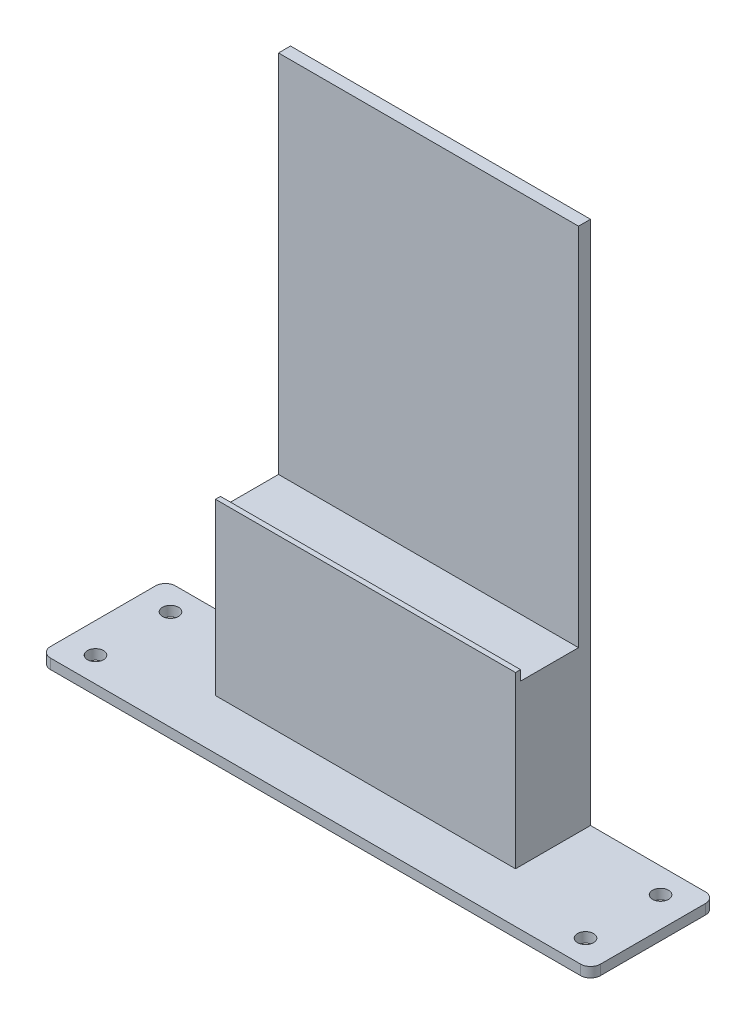
SolidWorks part; units mm, degrees
ref_plane "前视基准面" through (0, 0, 0) normal (0, 0, 1) x (1, 0, 0)
ref_plane "上视基准面" through (0, 0, 0) normal (0, 1, 0) x (1, 0, 0)
ref_plane "右视基准面" through (0, 0, 0) normal (1, 0, 0) x (0, 0, -1)
other "Configuration Table"
sketch "草图1" plane through (0, 0, 0) normal (0, 1, 0) x (1, 0, 0)
  line L0 (0, 0) -> (0, -50000) construction
  line L1 (-55, 12.5) -> (55, 12.5)
  line L2 (-55, 12.5) -> (-55, -12.5)
  line L3 (-55, -12.5) -> (55, -12.5)
  line L4 (55, 12.5) -> (55, -12.5)
  line L5 (-55, 12.5) -> (55, -12.5) construction
  line L6 (-55, -12.5) -> (55, 12.5) construction
  line L7 (0, 0) -> (-50000, 0) construction
  circle A0 centre (-49, 7.5) radius 1.6
  circle A1 centre (49, 7.5) radius 1.6
  circle A2 centre (49, -7.5) radius 1.6
  circle A3 centre (-49, -7.5) radius 1.6
  point P0 (0, 0)
  dimension "D3" = 3.2
  dimension "D1" = 110
  dimension "D2" = 25
  dimension "D4" = 15
  dimension "D5" = 98
extrude "凸台-拉伸1" add sketch "草图1" along normal blind 2
ref_plane "基准面1" through (0, 115, 0) normal (0, 1, 0) x (1, 0, 0)
sketch "草图2" plane through (0, 115, 0) normal (0, 1, 0) x (1, 0, 0)
  line L0 (55, 12.5) -> (-55, 12.5) construction
  line L1 (0, 0) -> (0, -50000) construction
  line L2 (-30, 12.5) -> (-30, -2.5)
  line L3 (-30, -2.5) -> (30, -2.5)
  line L4 (30, -2.5) -> (30, 12.5)
  line L5 (30, 12.5) -> (-30, 12.5)
  point P0 (-30, 12.5)
  point P6 (30, 12.5)
  dimension "D1" = 60
  dimension "D2" = 15
extrude "凸台-拉伸2" add sketch "草图2" against normal up to surface (113 mm away) up to face at (49, 2, 9.1)
sketch "草图3" plane through (30, 0, 0) normal (1, 0, 0) x (0, 0, -1)
  line L0 (-2.5, 2) -> (-2.5, 115) construction
  line L1 (-2.5, 36) -> (-1.5, 36)
  line L2 (-1.5, 34) -> (10.1, 34)
  line L3 (-1.5, 36) -> (-1.5, 34)
  line L4 (10.1, 34) -> (10.1, 113)
  line L5 (10.1, 113) -> (-1.5, 113)
  line L6 (-1.5, 113) -> (-1.5, 111)
  line L7 (-1.5, 111) -> (-2.5, 111)
  line L8 (-2.5, 36) -> (-2.5, 111)
  line L10 (-12.5, 0) -> (12.5, 0) construction
  line L11 (13.75, 115) -> (-13.75, 115) construction
  line L12 (12.5, 2) -> (12.5, 115) construction
  point P0 (-2.5, 36)
  point P1 (-2.5, 111)
  point P7 (-2.5, 115)
  point P16 (12.5, 115)
  dimension "D1" = 75
  dimension "D2" = 1
  dimension "D3" = 2
  dimension "D4" = 11.6
  dimension "D5" = 79
  dimension "D6" = 11.6
  dimension "D7" = 2
  dimension "D8" = 4
extrude "切除-拉伸1" cut sketch "草图3" against normal up to surface (60 mm away) up to face at (-30, 58.5, -5)
fillet "圆角1" radius 2 1 edges at (55, 1, 12.5)
fillet "圆角2" radius 2 1 edges at (55, 1, -12.5)
fillet "圆角3" radius 2 1 edges at (-55, 1, -12.5)
fillet "圆角4" radius 2 1 edges at (-55, 1, 12.5)
ref_plane "基准面3" through (0, 107, 0) normal (0, 1, 0) x (1, 0, 0)
sketch "草图7" plane through (30, 0, 0) normal (1, 0, 0) x (0, 0, -1)
  line L0 (10.1254, 107) -> (10.1, 113)
  line L1 (13.75, 107) -> (-13.75, 107) construction
  line L2 (10.1, 113) -> (-1.5, 113)
  line L3 (-1.5, 113) -> (-1.5, 110)
  line L4 (-1.5, 110) -> (-2.5724, 110)
  line L5 (-2.5724, 110) -> (-2.5724, 115)
  line L6 (13.75, 115) -> (-13.75, 115) construction
  line L7 (-2.5724, 115) -> (12.5, 115)
  line L8 (12.5, 2) -> (12.5, 115) construction
  line L9 (12.5, 115) -> (12.5, 107)
  line L10 (12.5, 107) -> (10.1254, 107)
extrude "切除-拉伸3" cut sketch "草图7" against normal through all
sketch "草图8" plane through (0, 0, -10.1) normal (0, 0, 1) x (1, 0, 0)
  line L0 (-30, 113) -> (-30, 107)
  line L1 (13.75, 107) -> (-13.75, 107) construction
  line L2 (-30, 34) -> (-30, 113) construction
  line L3 (-30, 107) -> (30, 107)
  line L4 (30, 34) -> (30, 113) construction
  line L5 (30, 107) -> (30, 113)
  line L6 (30, 113) -> (-30, 113)
extrude "切除-拉伸4" cut sketch "草图8" against normal through all
